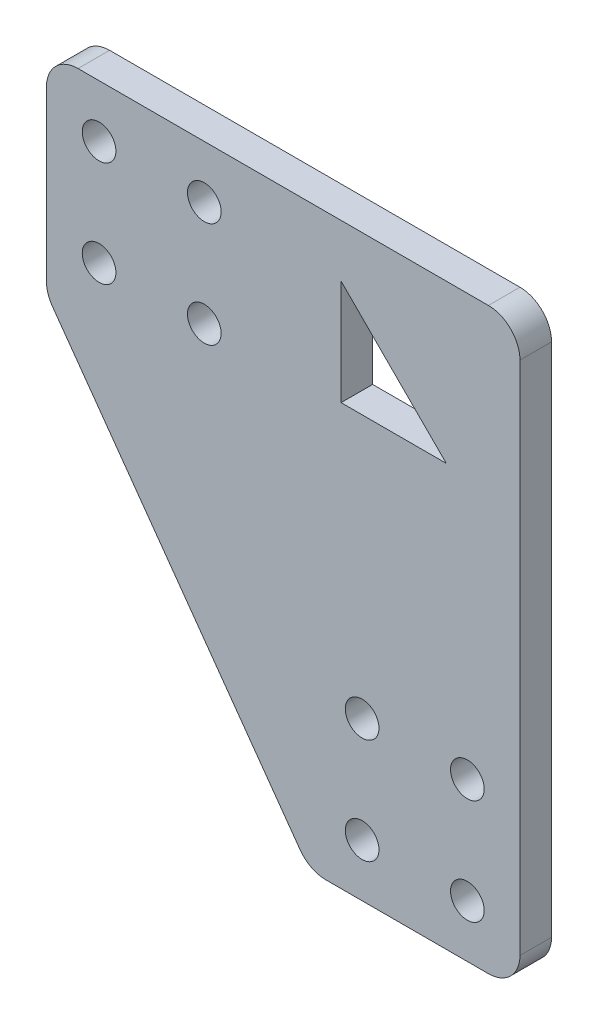
SolidWorks part; units mm, degrees
ref_plane "前视基准面" through (0, 0, 0) normal (0, 0, 1) x (1, 0, 0)
ref_plane "上视基准面" through (0, 0, 0) normal (0, 1, 0) x (1, 0, 0)
ref_plane "右视基准面" through (0, 0, 0) normal (1, 0, 0) x (0, 0, -1)
other "Configuration Table"
sketch "草图1" plane through (0, 0, 0) normal (0, 0, 1) x (1, 0, 0)
  line L0 (0, 0) -> (45, 0)
  line L3 (45, -55) -> (25, -55)
  line L4 (25, -55) -> (0, -20)
  line L5 (0, -20) -> (0, 0)
  line L6 (35, 0) -> (35, -55) construction
  line L7 (0, -10) -> (35, -10) construction
  line L8 (10, -10) -> (10, 0) construction
  line L9 (35, -45) -> (17.8571, -45) construction
  line L10 (28, -5) -> (28, -15)
  line L11 (28, -15) -> (38, -15)
  line L12 (38, -15) -> (28, -5)
  line L16 (45, 0) -> (45, -55)
  circle A0 centre (5, -5) radius 1.6
  circle A1 centre (15, -5) radius 1.6
  circle A2 centre (15, -15) radius 1.6
  circle A3 centre (5, -15) radius 1.6
  circle A8 centre (30, -50) radius 1.6
  circle A9 centre (40, -50) radius 1.6
  circle A10 centre (40, -40) radius 1.6
  circle A11 centre (30, -40) radius 1.6
  dimension "D8" = 3.2
  dimension "D11" = 3.2
  dimension "D2" = 20
  dimension "D3" = 20
  dimension "D4" = 45
  dimension "D5" = 55
  dimension "D6" = 10
  dimension "D7" = 10
  dimension "D9" = 5
  dimension "D10" = 5
  dimension "D12" = 5
  dimension "D13" = 5
  dimension "D14" = 10
  dimension "D15" = 10
  dimension "D19" = 7
extrude "凸台-拉伸1" add sketch "草图1" along normal blind 3
fillet "圆角1" radius 3 5 edges at (25, -55, 1.5) (45, -55, 1.5) (45, 0, 1.5) (0, -20, 1.5) (0, 0, 1.5)
